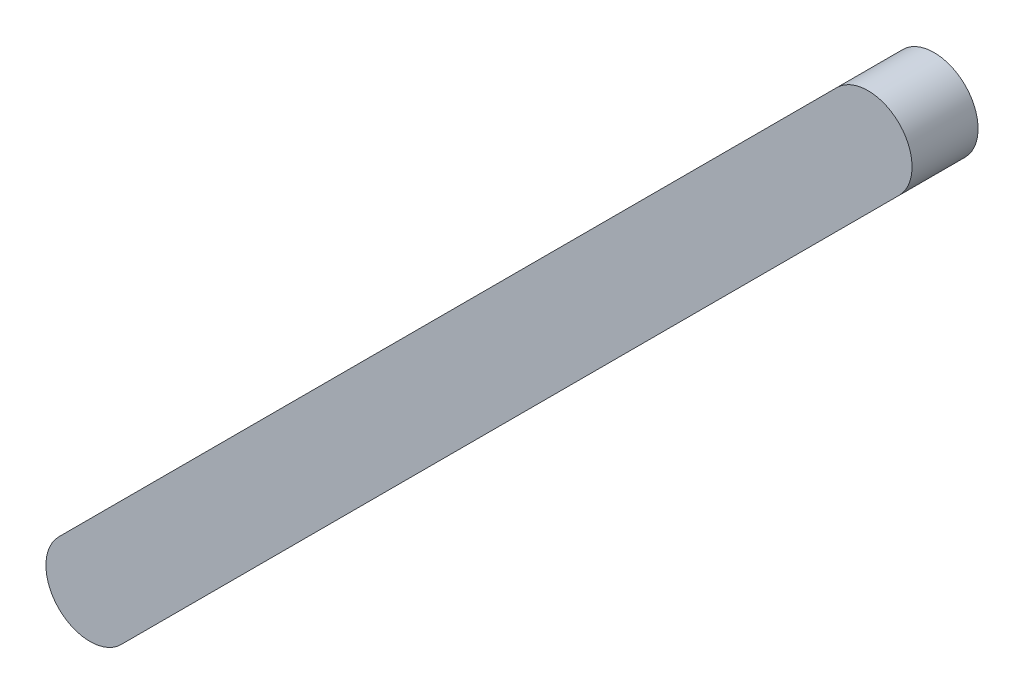
SolidWorks part; units mm, degrees
ref_plane "Front Plane" through (0, 0, 0) normal (0, 0, 1) x (1, 0, 0)
ref_plane "Top Plane" through (0, 0, 0) normal (0, 1, 0) x (1, 0, 0)
ref_plane "Right Plane" through (0, 0, 0) normal (1, 0, 0) x (0, 0, -1)
sketch "Sketch1" plane through (0, 0, 0) normal (0, 0, 1) x (1, 0, 0)
  line L0 (0, 0) -> (35.3553, 35.3553) construction
  line L1 (-1.4142, 1.4142) -> (33.9411, 36.7696)
  line L2 (1.4142, -1.4142) -> (36.7696, 33.9411)
  line L3 (0, 0) -> (10.4289, 0) construction
  arc A0 (-1.4142, 1.4142) -> (1.4142, -1.4142) centre (0, 0) ccw
  arc A1 (36.7696, 33.9411) -> (33.9411, 36.7696) centre (35.3553, 35.3553) ccw
  point P3 (17.6777, 17.6777)
  dimension "D2" = 2
  dimension "D1" = 50
  dimension "D3" = 45
extrude "Boss-Extrude1" add sketch "Sketch1" along normal blind 3
